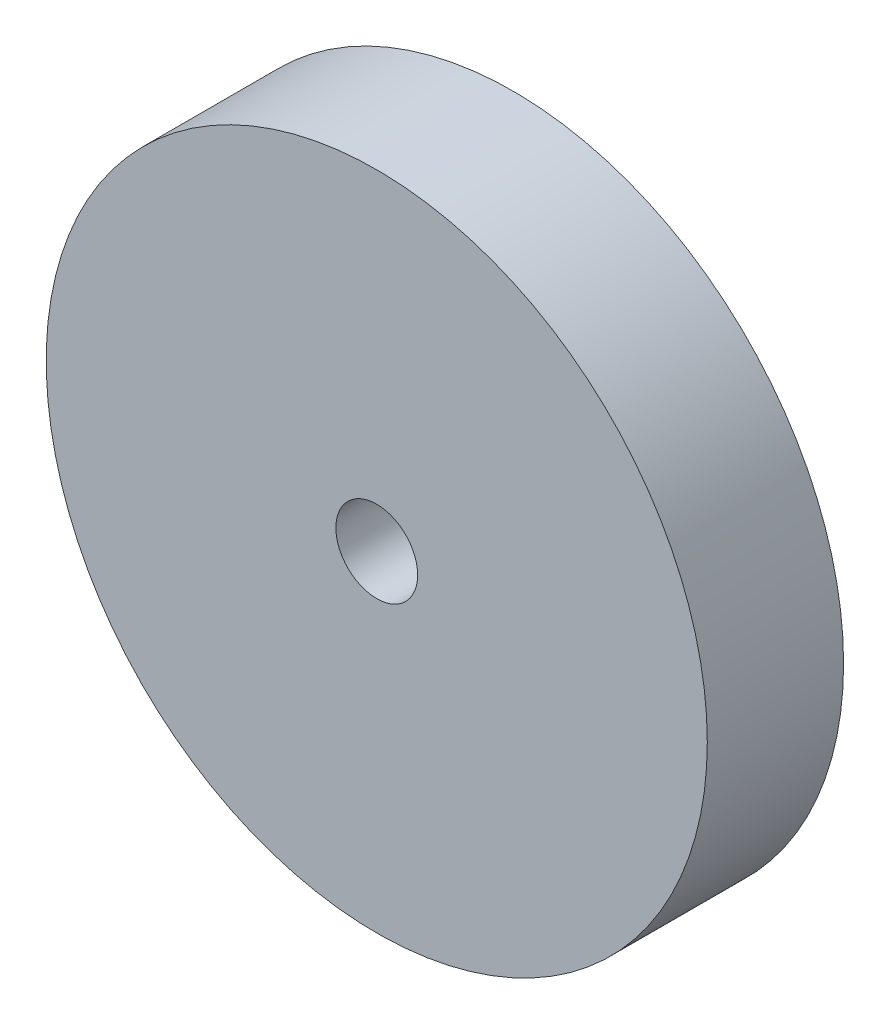
SolidWorks part; units mm, degrees
ref_plane "Front Plane" through (0, 0, 0) normal (0, 0, 1) x (1, 0, 0)
ref_plane "Top Plane" through (0, 0, 0) normal (0, 1, 0) x (1, 0, 0)
ref_plane "Right Plane" through (0, 0, 0) normal (1, 0, 0) x (0, 0, -1)
sketch "Sketch1" plane through (0, 0, 0) normal (0, 0, 1) x (1, 0, 0)
  circle A0 centre (0, 0) radius 48.5
  circle A1 centre (0, 0) radius 6
  dimension "D1" = 97
  dimension "D2" = 12
extrude "Boss-Extrude1" add sketch "Sketch1" along normal blind 20
